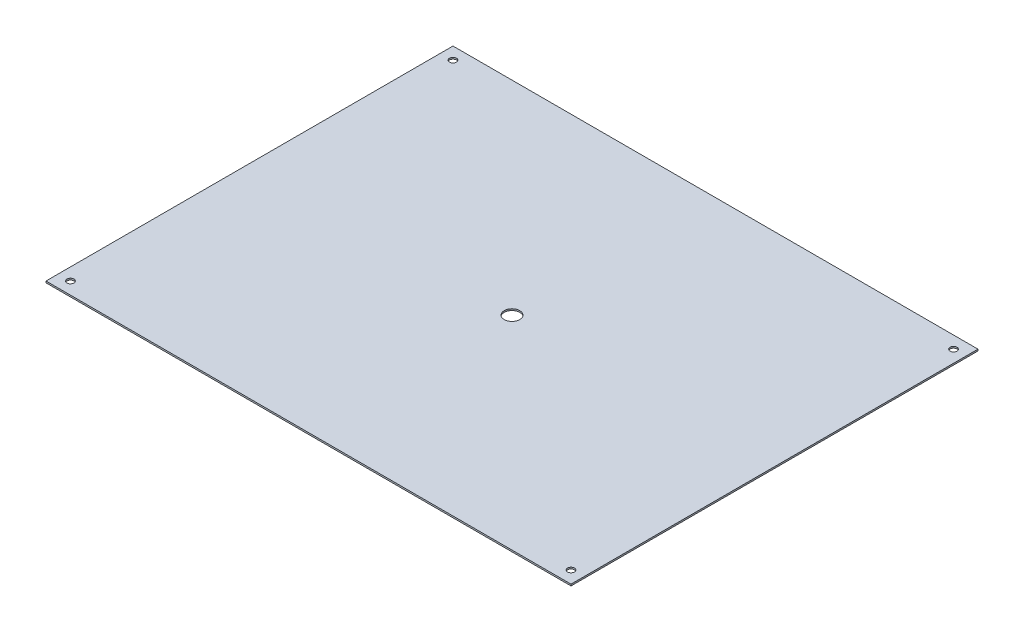
SolidWorks part; units mm, degrees
ref_plane "Front Plane" through (0, 0, 0) normal (0, 0, 1) x (1, 0, 0)
ref_plane "Top Plane" through (0, 0, 0) normal (0, 1, 0) x (1, 0, 0)
ref_plane "Right Plane" through (0, 0, 0) normal (1, 0, 0) x (0, 0, -1)
sketch "Sketch1" plane through (0, 0, 0) normal (0, 0, 1) x (1, 0, 0)
  line L0 (0, 0.3969) -> (0, -0.3969)
  line L1 (-152.4, 0) -> (152.4, 0) construction
  point P6 (0, 0)
  dimension "Width" = 304.8
  dimension "Thk" = 0.7937
sketch "Sketch2" plane through (0, 0, 0) normal (1, 0, 0) x (0, 0, -1)
  line L0 (152.4, 0) -> (-152.4, 0)
  point P4 (0, 0)
  dimension "Length" = 304.8
sketch "Sketch3" plane through (0, 0, 0) normal (0, 0, 1) x (1, 0, 0)
  line L1 (152.4, 0.3969) -> (-152.4, 0.3969)
  line L2 (152.4, 0.3969) -> (152.4, -0.3969)
  line L3 (152.4, -0.3969) -> (-152.4, -0.3969)
  line L4 (-152.4, 0.3969) -> (-152.4, -0.3969)
  line L5 (152.4, 0.3969) -> (-152.4, -0.3969) construction
  line L6 (152.4, -0.3969) -> (-152.4, 0.3969) construction
  point P0 (0, 0)
extrude "Boss-Extrude1" add sketch "Sketch3" along normal up to vertex (152.4 mm away) and the other way up to vertex (152.4 mm away) up to point (0, 0, 152.4) other way up to point (0, 0, -152.4)
sketch "Sketch4" plane through (0, 0.3969, 0) normal (0, 1, 0) x (1, 0, 0)
  line L1 (-129, 100) -> (129, 100)
  line L2 (-129, 100) -> (-129, -100)
  line L3 (-129, -100) -> (129, -100)
  line L4 (129, 100) -> (129, -100)
  line L5 (-129, 100) -> (-129, -100) construction
extrude "Fit2Enclosure" cut sketch "Sketch4" against normal up to next (0.7937 mm away) flip side to cut
hole_wizard "CubeMountHoles" positions "Sketch6" profile "Sketch7" hole size "M3" standard "ANSI Metric" end condition up to next
sketch "Sketch6" plane through (0, 0.3969, 0) normal (0, 1, 0) x (1, 0, 0)
  point P0 (-123, 94)
  point P3 (123, 94)
  point P6 (123, -94)
  point P9 (-122.975, -94)
sketch "Sketch7" plane through (-123, 0.3969, -94) normal (1, 0, 0) x (0, 0, 1)
  line L0 (0, 0) -> (0, 0.7937)
  line L1 (0, 0.7937) -> (1.7, 0.7937)
  line L2 (1.7, 0.7937) -> (1.7, 0)
  line L5 (1.7, 0) -> (0, 0)
  line L11 (0, -6.35) -> (0, 107.95) construction
  dimension "Thru Hole Dia." = 3.4
  dimension "Thru Hole Depth" = 0.7938
sketch "Sketch8" plane through (0, 0.3969, 0) normal (0, 1, 0) x (1, 0, 0)
  line L1 (0, 465.5803) -> (0, 325.8803) construction
  line L2 (-188.8422, 0) -> (-49.1422, 0) construction
  circle A0 centre (0, 0) radius 3.81
  dimension "D1" = 7.62
extrude "DrainHole" cut sketch "Sketch8" against normal up to next
